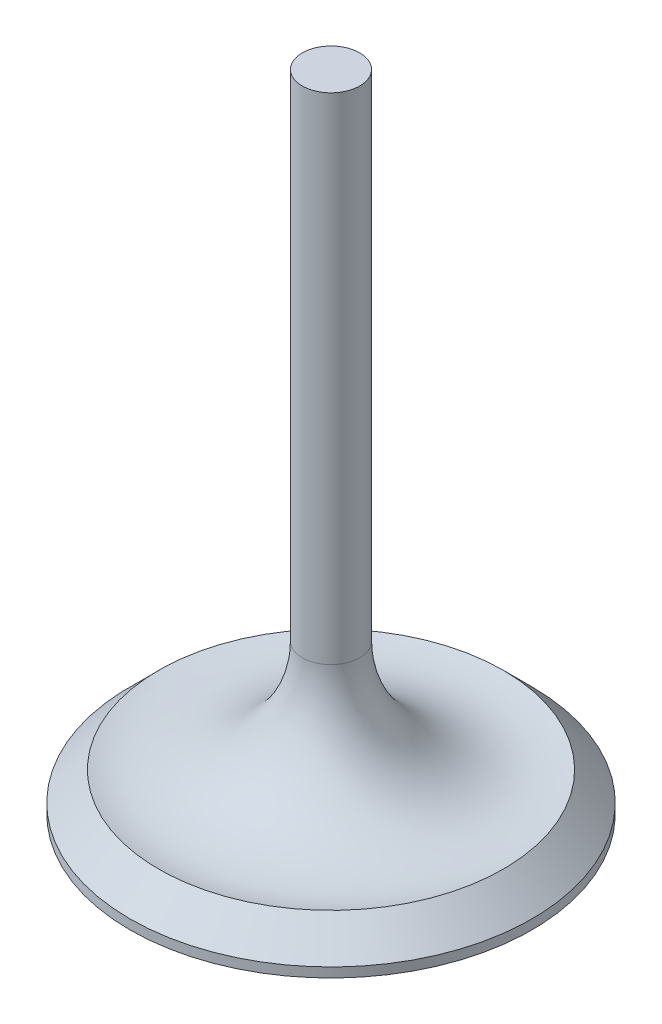
SolidWorks part; units mm, degrees
ref_plane "Front Plane" through (0, 0, 0) normal (0, 0, 1) x (1, 0, 0)
ref_plane "Top Plane" through (0, 0, 0) normal (0, 1, 0) x (1, 0, 0)
ref_plane "Right Plane" through (0, 0, 0) normal (1, 0, 0) x (0, 0, -1)
sketch "Sketch1" plane through (0, 0, 0) normal (0, 0, 1) x (1, 0, 0)
  line L0 (0, 0) -> (0, 85.55)
  line L1 (0, 85.55) -> (3.81, 85.55)
  line L2 (3.81, 85.55) -> (3.81, 19.849)
  line L3 (22.86, 5.08) -> (26.67, 1.27)
  line L4 (26.67, 1.27) -> (26.67, 0)
  line L5 (26.67, 0) -> (0, 0)
  arc A0 (3.81, 19.849) -> (22.86, 5.08) centre (19.06, 19.849) ccw
  point P8 (10.0617, 54.9218)
  dimension "D6" = 15.25
  dimension "D1" = 85.55
  dimension "D2" = 26.67
  dimension "D3" = 1.27
  dimension "D4" = 3.81
  dimension "D5" = 45
  dimension "D7" = 3.81
revolve "Revolve1" add sketch "Sketch1" angle 360 about L0
